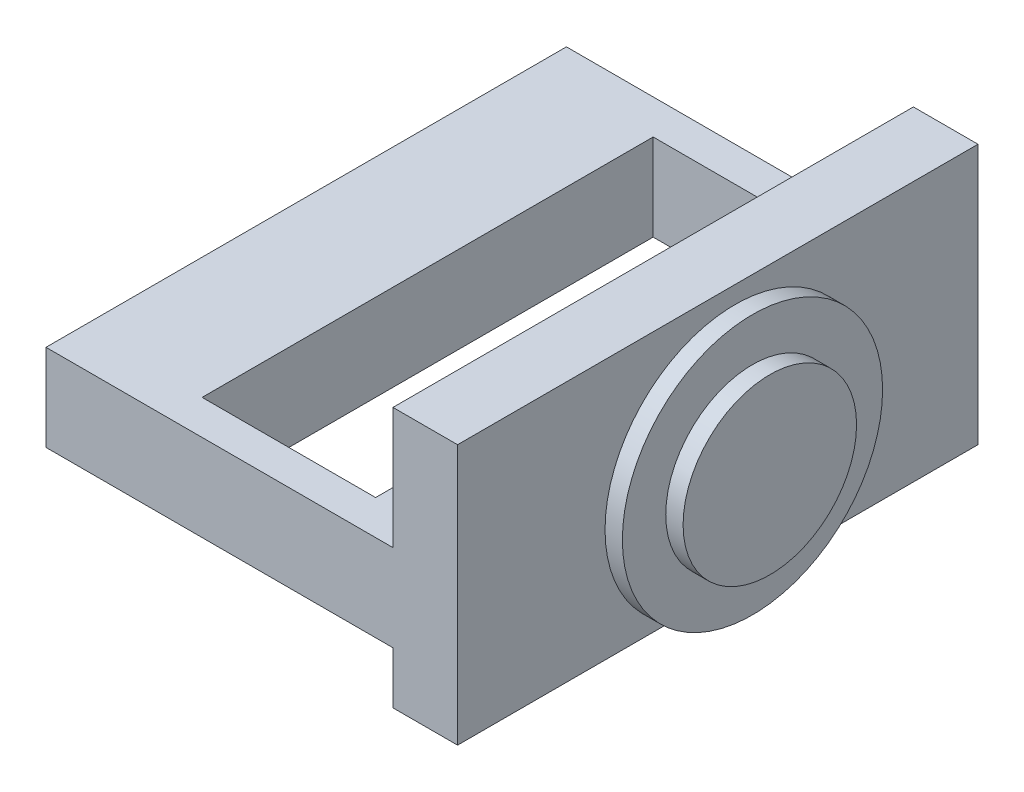
SolidWorks part; units mm, degrees
ref_plane "Front Plane" through (0, 0, 0) normal (0, 0, 1) x (1, 0, 0)
ref_plane "Top Plane" through (0, 0, 0) normal (0, 1, 0) x (1, 0, 0)
ref_plane "Right Plane" through (0, 0, 0) normal (1, 0, 0) x (0, 0, -1)
sketch "Sketch1" plane through (0, 0, 0) normal (0, 0, 1) x (1, 0, 0)
  line L0 (-14.1648, 3.151) -> (-14.1648, -1.849)
  line L1 (-14.1648, -1.849) -> (5.8352, -1.849)
  line L2 (5.8352, -1.849) -> (5.8352, -4.849)
  line L3 (5.8352, -4.849) -> (9.56, -4.849)
  line L4 (9.56, -4.849) -> (9.56, 10.151)
  line L5 (9.56, 10.151) -> (5.8352, 10.151)
  line L6 (5.8352, 10.151) -> (5.8352, 3.151)
  line L7 (5.8352, 3.151) -> (-14.1648, 3.151)
  dimension "D1" = 5
  dimension "D2" = 20
  dimension "D3" = 20
  dimension "D4" = 15
  dimension "D5" = 7
extrude "Boss-Extrude1" add sketch "Sketch1" along normal blind 30
sketch "Sketch3" plane through (0, 3.151, 0) normal (0, 1, 0) x (1, 0, 0)
  line L0 (2.8352, -2) -> (2.8352, -28)
  line L1 (2.8352, -28) -> (-7.1648, -28)
  line L2 (-7.1648, -28) -> (-7.1648, -2)
  line L3 (-7.1648, -2) -> (2.8352, -2)
  line L4 (5.8352, 0) -> (-14.1648, 0) construction
  line L5 (-14.1648, -30) -> (-14.1648, 0) construction
  dimension "D1" = 26
  dimension "D2" = 2
  dimension "D3" = 10
  dimension "D4" = 7
extrude "Cut-Extrude1" cut sketch "Sketch3" against normal blind 5
sketch "Sketch6" plane through (9.56, 0, 0) normal (1, 0, 0) x (0, 0, -1)
  circle A3 centre (-15, 2.651) radius 5
extrude "Boss-Extrude2" add sketch "Sketch6" along normal blind 1
sketch "Sketch7" plane through (10.56, 0, 0) normal (1, 0, 0) x (0, 0, -1)
  circle A0 centre (-15, 2.651) radius 7.5
  dimension "D1" = 15
extrude "Boss-Extrude3" add sketch "Sketch7" along normal blind 1
sketch "Sketch8" plane through (11.56, 0, 0) normal (1, 0, 0) x (0, 0, -1)
  circle A0 centre (-15, 2.651) radius 5
  dimension "D1" = 10
extrude "Boss-Extrude4" add sketch "Sketch8" along normal blind 1
